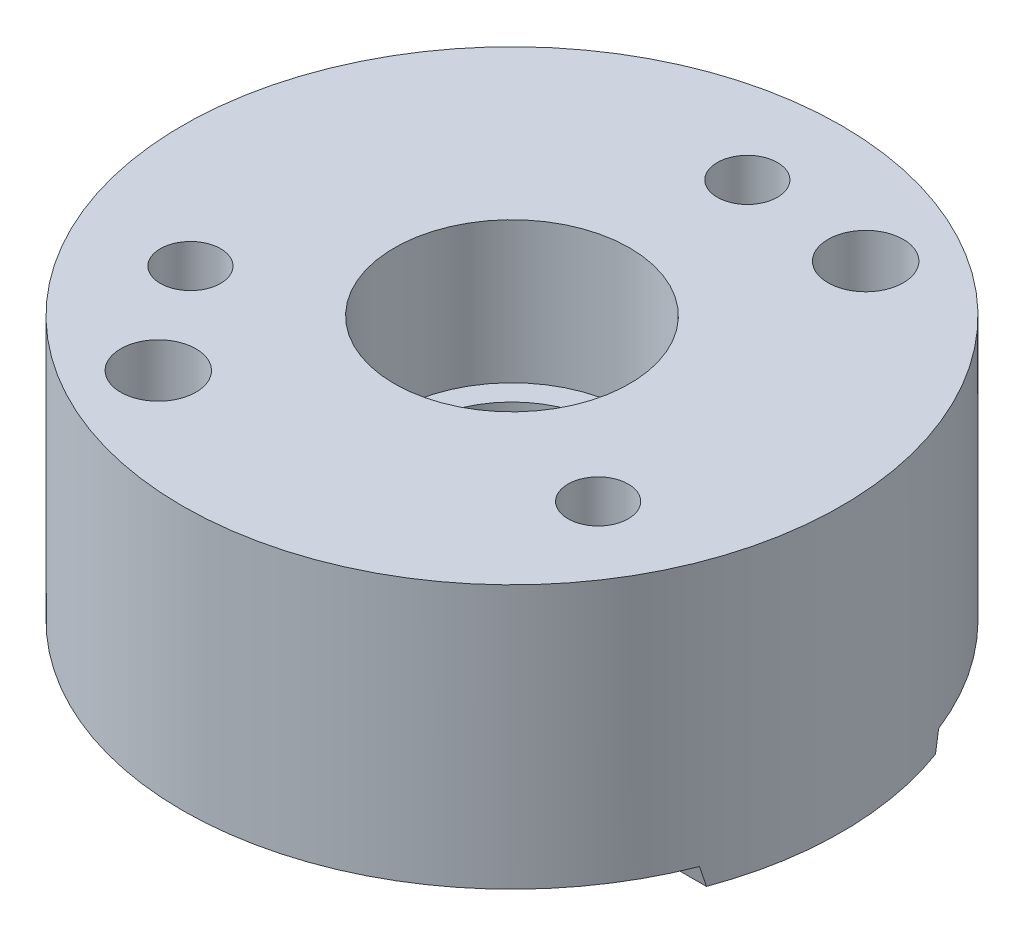
SolidWorks part; units mm, degrees
material "K110"
ref_plane "Front Plane" through (0, 0, 0) normal (0, 0, 1) x (1, 0, 0)
ref_plane "Top Plane" through (0, 0, 0) normal (0, 1, 0) x (1, 0, 0)
ref_plane "Right Plane" through (0, 0, 0) normal (1, 0, 0) x (0, 0, -1)
sketch "Sketch1" plane through (0, 0, 0) normal (0, 1, 0) x (1, 0, 0)
  circle A0 centre (0, 0) radius 35
  circle A1 centre (0, 0) radius 10
  dimension "D1" = 20
  dimension "D2" = 70
extrude "Boss-Extrude1" add sketch "Sketch1" against normal blind 30
sketch "Sketch4" plane through (0, 0, 0) normal (0, 1, 0) x (1, 0, 0)
  circle A0 centre (0, 0) radius 12.5
  dimension "D1" = 25
extrude "Cut-Extrude2" cut sketch "Sketch4" against normal blind 15
hole_wizard "CBORE for M6 Hex Socket Head Cap Screw1" positions "Sketch15" profile "Sketch8" counterbore size "M6" standard "ISO" end condition through all
sketch "Sketch15" plane through (0, -30, 0) normal (0, -1, 0) x (-1, 0, 0)
  line L0 (0, 25) -> (0, 0) construction
  line L1 (0, 0) -> (-21.6506, -12.5) construction
  line L3 (0, 0) -> (21.6506, -12.5) construction
  circle A0 centre (0, 0) radius 25 construction
  point P0 (0, 25)
  point P2 (21.6506, -12.5)
  point P4 (-21.6506, -12.5)
  dimension "D1" = 50
  dimension "D2" = 120
  dimension "D3" = 120
sketch "Sketch8" plane through (0, -30, -25) normal (1, 0, 0) x (0, 0, -1)
  line L0 (0, 0) -> (0, 30)
  line L1 (0, 30) -> (3.2, 30)
  line L3 (3.2, 30) -> (3.2, 8.4)
  line L4 (3.2, 8.4) -> (5.5, 8.4)
  line L5 (5.5, 8.4) -> (5.5, 0)
  line L7 (5.5, 0) -> (0, 0)
  line L11 (0, -6.35) -> (0, 107.95) construction
  dimension "Thru Hole Dia." = 6.4
  dimension "Thru Hole Depth" = 30
  dimension "C'Bore Dia." = 11
  dimension "C'Bore Depth" = 8.4
hole_wizard "Ø8.0mm Dowel Hole1" positions "Sketch17" profile "Sketch12" hole size "Ø8.0" standard "ISO" end condition through all
sketch "Sketch17" plane through (0, -30, 0) normal (0, -1, 0) x (-1, 0, 0)
  line L0 (-13.75, 23.8157) -> (13.75, -23.8157) construction
  line L1 (0, 35) -> (0, -35) construction
  circle A0 centre (0, 0) radius 27.5 construction
  circle A1 centre (0, 0) radius 35 construction
  point P0 (13.75, -23.8157)
  point P2 (-13.75, 23.8157)
  point P26 (0, 0)
  dimension "D1" = 55
  dimension "D2" = 30
sketch "Sketch12" plane through (-13.75, -30, 23.8157) normal (1, 0, 0) x (0, 0, -1)
  line L0 (0, 0) -> (0, 30)
  line L1 (0, 30) -> (4, 30)
  line L2 (4, 30) -> (4, 0)
  line L5 (4, 0) -> (0, 0)
  line L11 (0, -6.35) -> (0, 107.95) construction
  dimension "Thru Hole Dia." = 8
  dimension "Thru Hole Depth" = 30
sketch "Sketch14" plane through (0, -30, 0) normal (0, -1, 0) x (1, 0, 0)
  line L0 (-58.6405, -12.7) -> (-15.5229, -12.7) construction
  line L1 (-35, 12.7) -> (35, 12.7)
  line L2 (-35, 12.7) -> (-35, -12.7)
  line L3 (-35, -12.7) -> (35, -12.7)
  line L4 (35, 12.7) -> (35, -12.7)
  line L5 (-35, 12.7) -> (35, -12.7) construction
  line L6 (-35, -12.7) -> (35, 12.7) construction
  circle A0 centre (0, 0) radius 35 construction
  point P0 (0, 0)
extrude "Cut-Extrude3" cut sketch "Sketch14" against normal blind 2 flip side to cut
sketch "Sketch16" plane through (0, -30, 0) normal (0, -1, 0) x (1, 0, 0)
  circle A0 centre (22.5, 0) radius 4.25
  dimension "D1" = 8.5
sketch "Sketch18" plane through (0, -30, 0) normal (0, -1, 0) x (1, 0, 0)
  circle A1 centre (-13.665, 0) radius 2.1
  dimension "D1" = 4.2
extrude "Cut-Extrude5" cut sketch "Sketch18" against normal blind 3
sketch "Sketch19" plane through (0, 0, 0) normal (1, 0, 0) x (0, 0, -1)
  line L2 (-12.7, -28) -> (-12.1641, -30)
  line L3 (-12.7, -30) -> (12.7, -30) construction
  line L4 (-12.1641, -30) -> (-12.7, -30)
  line L5 (-12.7, -30) -> (-12.7, -28)
  line L6 (12.7, -28) -> (12.1641, -30)
  line L7 (12.1641, -30) -> (12.7, -30)
  line L8 (12.7, -30) -> (12.7, -28)
  dimension "D1" = 15
  dimension "D2" = 15
extrude "Cut-Extrude6" cut sketch "Sketch19" against normal through all both and the other way through all
sketch "Sketch20" plane through (0, -30, 0) normal (0, -1, 0) x (1, 0, 0)
  line L0 (-16.1609, 12.1641) -> (16.1609, 12.1641) construction
  line L1 (-12.5811, 12.1641) -> (12.5811, 12.1641)
  line L2 (-32.8182, -12.1641) -> (32.8182, -12.1641) construction
  line L3 (-12.5811, -12.1641) -> (12.5811, -12.1641)
  arc A0 (12.5811, 12.1641) -> (-12.5811, 12.1641) centre (0, 0) ccw
  arc A1 (-12.5811, -12.1641) -> (12.5811, -12.1641) centre (0, 0) ccw
  dimension "D1" = 35
extrude "Boss-Extrude2" add sketch "Sketch20" against normal up to surface (2 mm away) up to face at (13.75, -28, -27.8157)
draft "Draft1" type of draft neutral plane draft angle 15 faces to draft 2 face at (0, -28.9945, 14.9675) face at (0, -28.9945, -14.9675) neutral plane through (0, -28, 0) neutral plane normal (0, -1, 0) parameters "D1"=15
fillet "Fillet1" radius 10 4 edges
